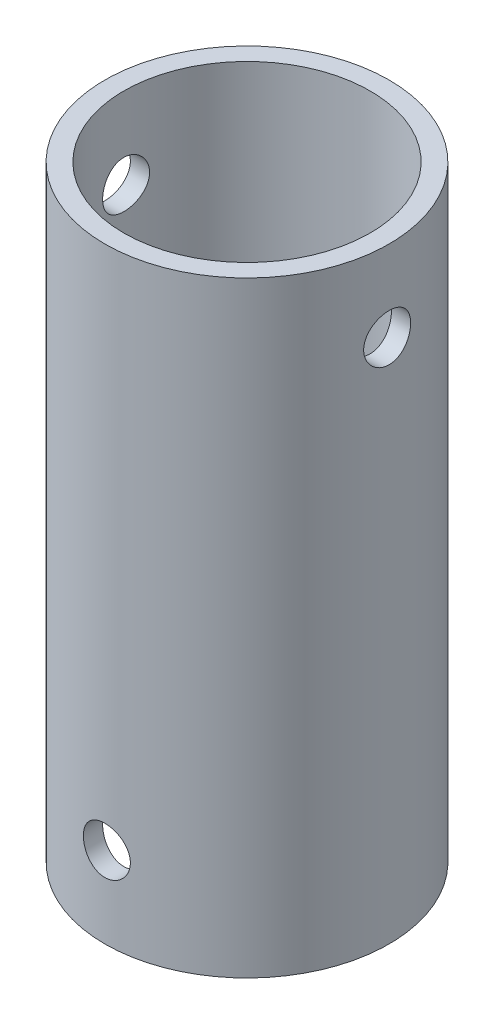
SolidWorks part; units mm, degrees
material "1023 Carbon Steel Sheet (SS)"
ref_plane "Front Plane" through (0, 0, 0) normal (0, 0, 1) x (1, 0, 0)
ref_plane "Top Plane" through (0, 0, 0) normal (0, 1, 0) x (1, 0, 0)
ref_plane "Right Plane" through (0, 0, 0) normal (1, 0, 0) x (0, 0, -1)
sketch "Sketch1" plane through (0, 0, 0) normal (0, 1, 0) x (1, 0, 0)
  circle A0 centre (0, 0) radius 16.25
  circle A1 centre (0, 0) radius 18.75
  dimension "D1" = 2.5
  dimension "D2" = 32.5
extrude "Boss-Extrude2" add sketch "Sketch1" along normal blind 80 contours A1 | A0
sketch "Sketch2" plane through (0, 0, 0) normal (0, 0, 1) x (1, 0, 0)
  circle A0 centre (0, 10.7) radius 3.1
  dimension "D2" = 6.2
  dimension "D1" = 10.7
extrude "Cut-Extrude1" cut sketch "Sketch2" against normal through all both and the other way through all
sketch "Sketch3" plane through (0, 0, 0) normal (1, 0, 0) x (0, 0, -1)
  line L0 (0, 55) -> (0, -55) construction
  line L1 (18.75, 80) -> (-18.75, 80) construction
  circle A0 centre (0, 69.3) radius 3.1
  dimension "D1" = 10.7
extrude "Cut-Extrude2" cut sketch "Sketch3" against normal through all both and the other way through all
